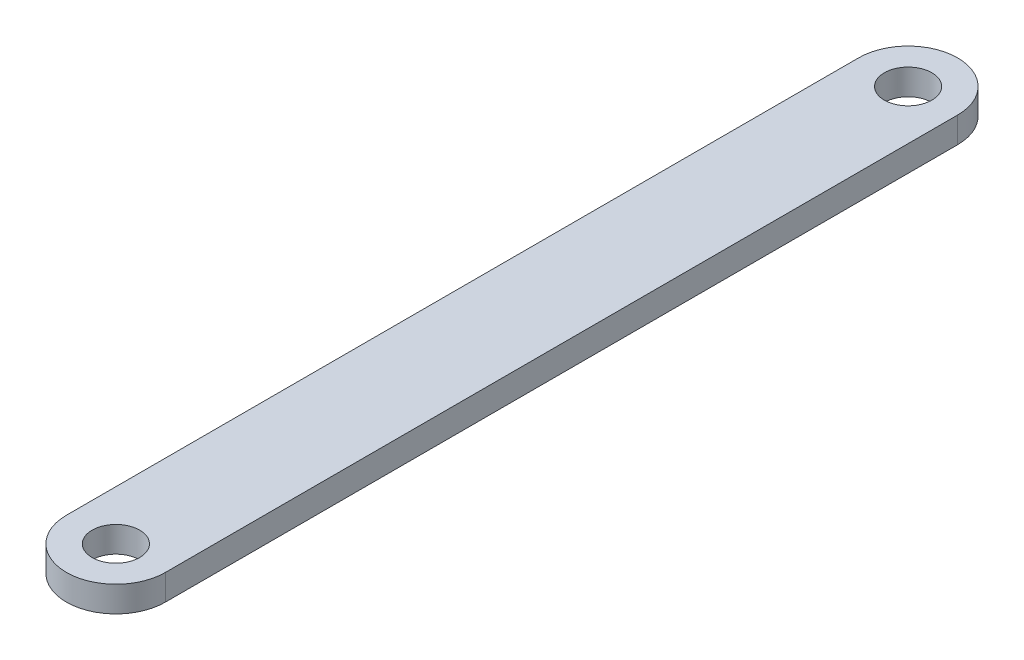
SolidWorks part; units mm, degrees
ref_plane "Front Plane" through (0, 0, 0) normal (0, 0, 1) x (1, 0, 0)
ref_plane "Top Plane" through (0, 0, 0) normal (0, 1, 0) x (1, 0, 0)
ref_plane "Right Plane" through (0, 0, 0) normal (1, 0, 0) x (0, 0, -1)
sketch "Sketch3" plane through (0, 0, 0) normal (0, 1, 0) x (1, 0, 0)
  line L0 (-12.5, 100) -> (-12.5, -100)
  line L1 (0, 0) -> (0, 36.4805) construction
  line L2 (12.5, 100) -> (12.5, -100)
  line L3 (0, 0) -> (18.4732, 0) construction
  arc A0 (12.5, 100) -> (-12.5, 100) centre (0, 100) ccw
  circle A2 centre (0, 100) radius 6
  circle A3 centre (0, -100) radius 6
  arc A4 (12.5, -100) -> (-12.5, -100) centre (0, -100) cw
  point P14 (0, 0)
  point P15 (-25.397, -112.5169)
  point P16 (-29.3257, 122.2215)
  dimension "D1" = 25
  dimension "D2" = 12
  dimension "D3" = 100
extrude "Boss-Extrude1" add sketch "Sketch3" along normal mid plane 6.5
